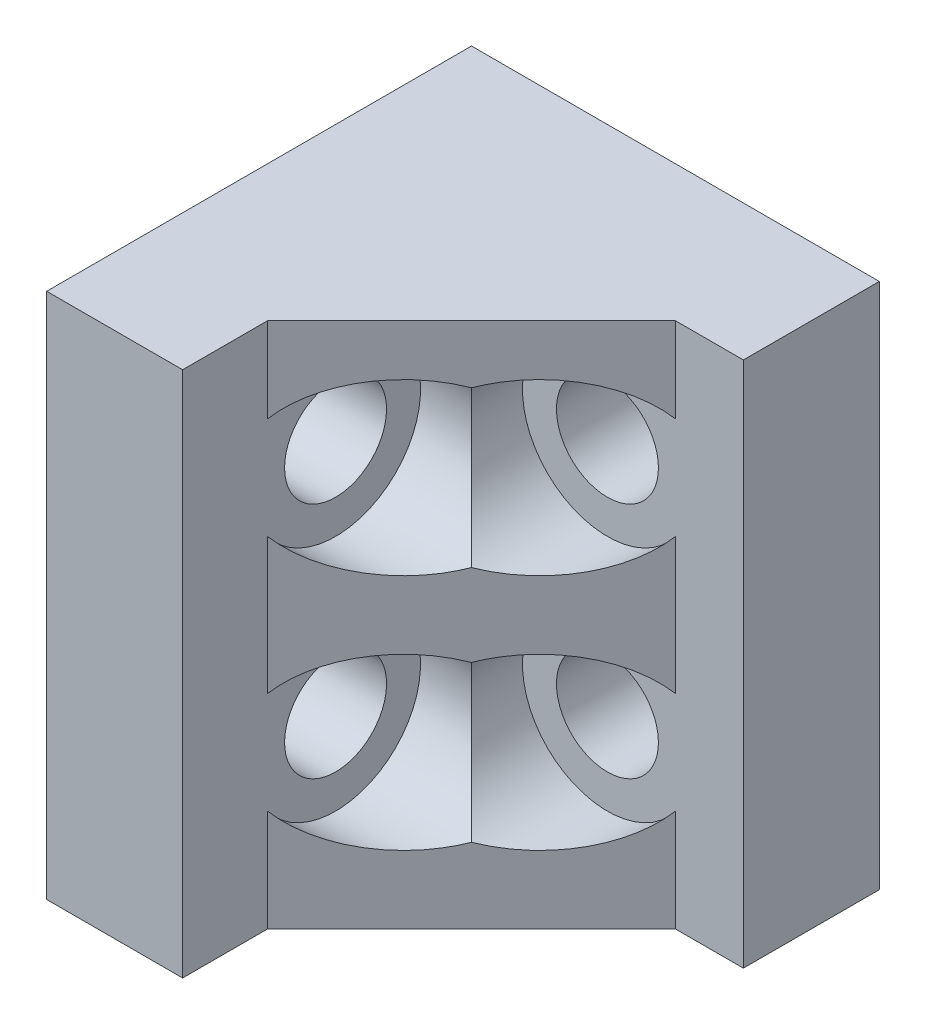
SolidWorks part; units mm, degrees
ref_plane "Front Plane" through (0, 0, 0) normal (0, 0, 1) x (1, 0, 0)
ref_plane "Top Plane" through (0, 0, 0) normal (0, 1, 0) x (1, 0, 0)
ref_plane "Right Plane" through (0, 0, 0) normal (1, 0, 0) x (0, 0, -1)
sketch "Sketch1" plane through (0, 0, 0) normal (0, 0, 1) x (1, 0, 0)
  line L2 (1.7804, 35.847) -> (13.7804, 35.847)
  line L3 (1.7804, 35.847) -> (1.7804, 20.347)
  line L4 (1.7804, 20.347) -> (13.7804, 20.347)
  line L5 (13.7804, 35.847) -> (13.7804, 20.347)
  dimension "D3" = 12
extrude "Boss-Extrude1" add sketch "Sketch1" along normal blind 4
sketch "Sketch2" plane through (0, 0, 4) normal (0, 0, 1) x (1, 0, 0)
  line L0 (13.7804, 35.847) -> (1.7804, 35.847) construction
  line L1 (1.7804, 20.347) -> (5.7804, 20.347)
  line L2 (1.7804, 20.347) -> (1.7804, 35.847)
  line L3 (1.7804, 35.847) -> (5.7804, 35.847)
  line L4 (5.7804, 20.347) -> (5.7804, 35.847)
  dimension "D1" = 4
extrude "Boss-Extrude2" add sketch "Sketch2" along normal up to vertex (8.5 mm away)
sketch "Sketch3" plane through (5.7804, 0, 0) normal (1, 0, 0) x (0, 0, -1)
  line L0 (0, 20.347) -> (0, 35.847) construction
  line L1 (-12.5, 35.847) -> (-4, 35.847) construction
  circle A0 centre (-8, 24.847) radius 1.5
  circle A1 centre (-8, 31.847) radius 1.5
  point P8 (-8.25, 35.847)
  dimension "D1" = 3
  dimension "D2" = 3
  dimension "D3" = 8
  dimension "D4" = 0
  dimension "D5" = 4
  dimension "D6" = 7
extrude "Cut-Extrude1" cut sketch "Sketch3" against normal blind 5
sketch "Sketch4" plane through (0, 0, 4) normal (0, 0, 1) x (1, 0, 0)
  line L1 (13.7804, 35.847) -> (5.7804, 35.847) construction
  line L2 (13.7804, 20.347) -> (13.7804, 35.847) construction
  circle A0 centre (9.7804, 24.847) radius 1.5
  circle A1 centre (9.7804, 31.847) radius 1.5
  dimension "D1" = 3
  dimension "D2" = 3
  dimension "D4" = 4
  dimension "D5" = 0
  dimension "D6" = 4
  dimension "D3" = 7
extrude "Cut-Extrude2" cut sketch "Sketch4" against normal blind 5
sketch "Sketch5" plane through (0, 35.847, 0) normal (0, 1, 0) x (1, 0, 0)
  line L0 (5.7804, -4) -> (5.7804, -10)
  line L1 (5.7804, -12.5) -> (5.7804, -4) construction
  line L2 (5.7804, -10) -> (11.7804, -4)
  line L3 (13.7804, -4) -> (5.7804, -4) construction
  line L4 (11.7804, -4) -> (5.7804, -4)
  dimension "D1" = 6
  dimension "D2" = 6
extrude "Boss-Extrude3" add sketch "Sketch5" against normal up to vertex (15.5 mm away)
sketch "Sketch6" plane through (13.7804, 0, 0) normal (1, 0, 0) x (0, 0, -1)
  line L3 (0, 35.847) -> (0, 20.347) construction
  line L5 (-12.5, 35.847) -> (0, 35.847) construction
  circle A0 centre (-8, 31.847) radius 2.5
  circle A1 centre (-8, 24.847) radius 2.5
  dimension "D1" = 5
  dimension "D2" = 5
  dimension "D3" = 8
  dimension "D4" = 7
  dimension "D5" = 4
  dimension "D6" = 0
extrude "Cut-Extrude3" cut sketch "Sketch6" against normal blind 8
sketch "Sketch7" plane through (0, 0, 12.5) normal (0, 0, 1) x (1, 0, 0)
  line L3 (13.7804, 20.347) -> (13.7804, 35.847) construction
  circle A0 centre (9.7804, 31.847) radius 2.5
  circle A1 centre (9.7804, 24.847) radius 2.5
  arc A2 (5.7804, 23.347) -> (5.7804, 26.347) centre (7.7804, 24.847) ccw construction
  arc A3 (5.7804, 30.347) -> (5.7804, 33.347) centre (7.7804, 31.847) ccw construction
  dimension "D1" = 5
  dimension "D2" = 0
  dimension "D3" = 0
  dimension "D4" = 0
  dimension "D5" = 4
extrude "Cut-Extrude4" cut sketch "Sketch7" against normal up to vertex (8.5 mm away)
